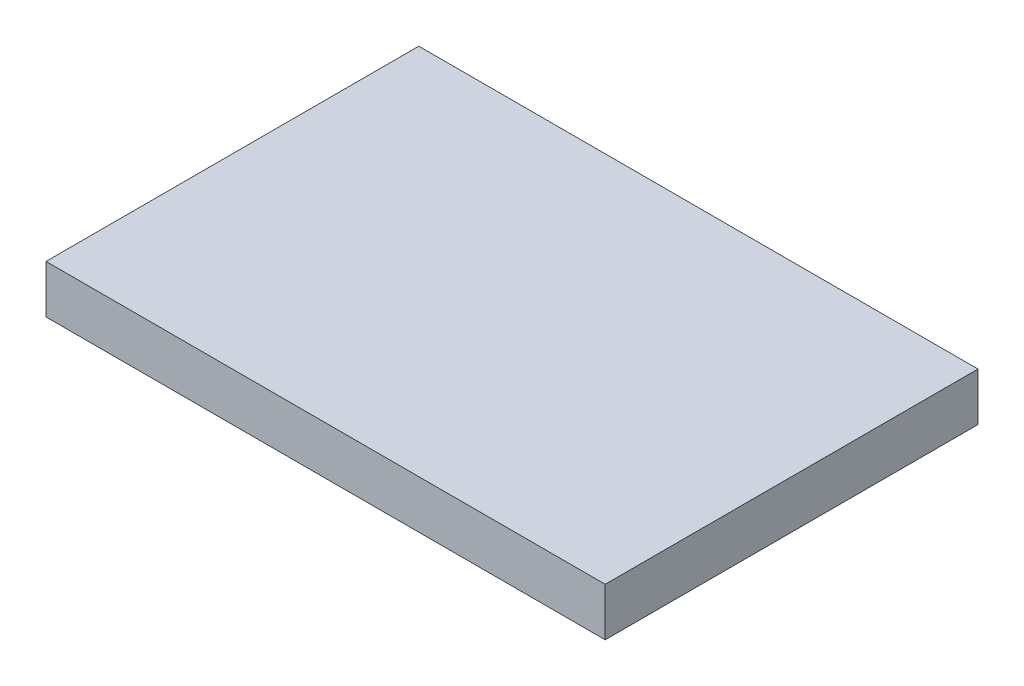
SolidWorks part; units mm, degrees
ref_plane "Front Plane" through (0, 0, 0) normal (0, 0, 1) x (1, 0, 0)
ref_plane "Top Plane" through (0, 0, 0) normal (0, 1, 0) x (1, 0, 0)
ref_plane "Right Plane" through (0, 0, 0) normal (1, 0, 0) x (0, 0, -1)
sketch "Sketch1" plane through (0, 0, 0) normal (0, 1, 0) x (1, 0, 0)
  line L1 (0, 0) -> (228.6, 0)
  line L2 (0, 0) -> (0, -12.7)
  line L3 (0, -12.7) -> (228.6, -12.7)
  line L4 (228.6, 0) -> (228.6, -12.7)
  dimension "D1" = 228.6
  dimension "D2" = 12.7
extrude "Boss-Extrude1" add sketch "Sketch1" against normal blind 0.8
sketch "Sketch2" [suppressed] plane through (0, 0, 0) normal (0, 1, 0) x (1, 0, 0)
  line L0 (228.6, -12.7) -> (228.6, 0) construction
  line L1 (0, -12.7) -> (228.6, -12.7)
  line L2 (0, -12.7) -> (0, -4.2)
  line L3 (0, -4.2) -> (228.6, -4.2)
  line L4 (228.6, -12.7) -> (228.6, -4.2)
  line L5 (228.6, 0) -> (0, 0) construction
  dimension "D1" = 4.2
extrude "Cut-Extrude1" [suppressed] cut sketch "Sketch2" against normal through all
sketch "Sketch3" [suppressed] plane through (0, 0, 0) normal (0, 1, 0) x (1, 0, 0)
  line L0 (228.6, -12.7) -> (228.6, 0) construction
  line L1 (0, -12.7) -> (228.6, -12.7)
  line L2 (0, -12.7) -> (0, -8.3)
  line L3 (0, -8.3) -> (228.6, -8.3)
  line L4 (228.6, -12.7) -> (228.6, -8.3)
  line L5 (228.6, 0) -> (0, 0) construction
  dimension "D1" = 8.3
extrude "Cut-Extrude2" [suppressed] cut sketch "Sketch3" against normal through all
sketch "Sketch4" [suppressed] plane through (0, 0, 0) normal (0, 1, 0) x (1, 0, 0)
  line L0 (228.6, 0) -> (0, 0) construction
  line L1 (228.6, -12.7) -> (4.2, -12.7)
  line L2 (228.6, -12.7) -> (228.6, 0)
  line L3 (228.6, 0) -> (4.2, 0)
  line L4 (4.2, -12.7) -> (4.2, 0)
  line L5 (0, 0) -> (0, -12.7) construction
  line L7 (4.2, -12.7) -> (0, -12.7)
  line L8 (4.2, -12.7) -> (4.2, -7.5)
  line L9 (4.2, -7.5) -> (0, -7.5)
  line L10 (0, -12.7) -> (0, -7.5)
  dimension "D1" = 4.2
  dimension "D2" = 7.5
extrude "Cut-Extrude3" [suppressed] cut sketch "Sketch4" against normal through all
sketch "Sketch5" [suppressed] plane through (0, 0, 0) normal (0, 1, 0) x (1, 0, 0)
  line L0 (228.6, 0) -> (0, 0) construction
  line L1 (228.6, -12.7) -> (9.3, -12.7)
  line L2 (228.6, -12.7) -> (228.6, 0)
  line L3 (228.6, 0) -> (9.3, 0)
  line L4 (9.3, -12.7) -> (9.3, 0)
  line L6 (0, -12.7) -> (9.3, -12.7)
  line L7 (0, -12.7) -> (0, -9.3)
  line L8 (0, -9.3) -> (9.3, -9.3)
  line L9 (9.3, -12.7) -> (9.3, -9.3)
  dimension "D1" = 9.3
  dimension "D2" = 9.3
extrude "Cut-Extrude4" [suppressed] cut sketch "Sketch5" against normal through all
sketch "Sketch6" plane through (0, -0.8, 0) normal (0, -1, 0) x (1, 0, 0)
  line L0 (0, 12.7) -> (228.6, 12.7) construction
  line L1 (228.6, 0) -> (9.3, 0)
  line L2 (228.6, 0) -> (228.6, 12.7)
  line L3 (228.6, 12.7) -> (9.3, 12.7)
  line L4 (9.3, 0) -> (9.3, 12.7)
  line L5 (228.6, 0) -> (0, 0) construction
  line L6 (0, 12.7) -> (9.3, 12.7)
  line L7 (0, 12.7) -> (0, 6.2)
  line L8 (0, 6.2) -> (9.3, 6.2)
  line L9 (9.3, 12.7) -> (9.3, 6.2)
  line M6 (0, 12.7) -> (0, 0)
  line M7 (0, 0) -> (228.6, 0)
  line M8 (228.6, 0) -> (228.6, 12.7)
  line M9 (228.6, 12.7) -> (0, 12.7)
  dimension "D1" = 9.3
  dimension "D2" = 6.2
extrude "Cut-Extrude5" cut sketch "Sketch6" against normal through all contours L4 M7 M8 M9 | L8 L4 M6 M9
sketch "Sketch7" [suppressed] plane through (0, -0.8, 0) normal (0, -1, 0) x (1, 0, 0)
  line L0 (0, 12.7) -> (228.6, 12.7) construction
  line L1 (228.6, 0) -> (8.5, 0)
  line L2 (228.6, 0) -> (228.6, 12.7)
  line L3 (228.6, 12.7) -> (8.5, 12.7)
  line L4 (8.5, 0) -> (8.5, 12.7)
  line L6 (0, 12.7) -> (8.5, 12.7)
  line L7 (0, 12.7) -> (0, 6.2)
  line L8 (0, 6.2) -> (8.5, 6.2)
  line L9 (8.5, 12.7) -> (8.5, 6.2)
  line L10 (228.6, 0) -> (0, 0) construction
  line M9 (0, 12.7) -> (0, 0)
  line M10 (0, 0) -> (228.6, 0)
  line M11 (228.6, 0) -> (228.6, 12.7)
  line M12 (228.6, 12.7) -> (0, 12.7)
  dimension "D1" = 8.5
  dimension "D2" = 6.2
extrude "Cut-Extrude6" [suppressed] cut sketch "Sketch7" against normal through all contours L4 M10 M11 M12 | L8 L4 M9 M12
